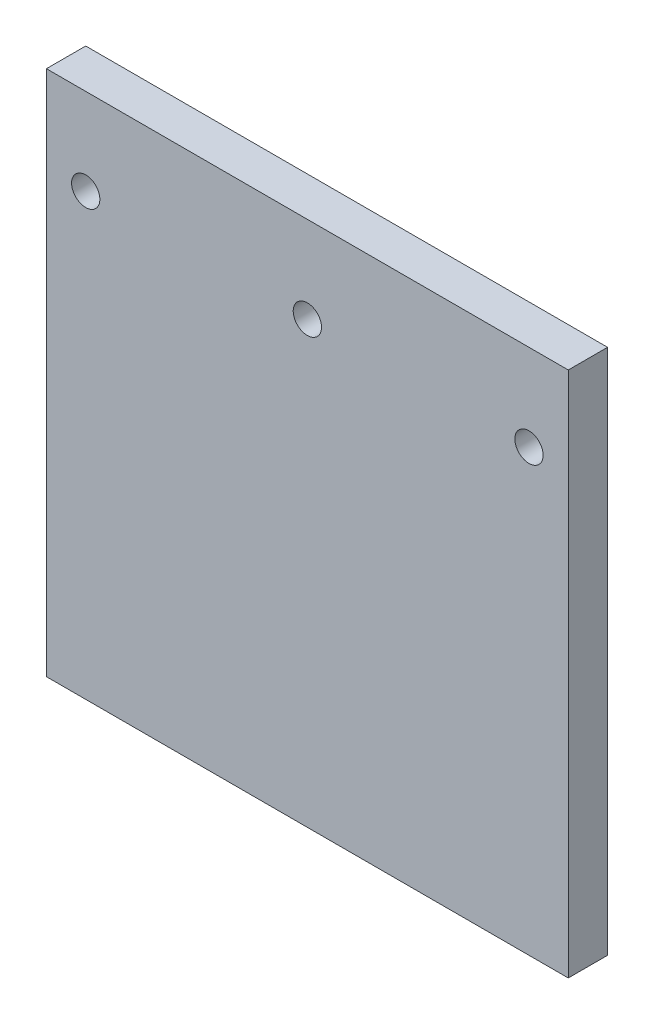
SolidWorks part; units mm, degrees
ref_plane "前视基准面" through (0, 0, 0) normal (0, 0, 1) x (1, 0, 0)
ref_plane "上视基准面" through (0, 0, 0) normal (0, 1, 0) x (1, 0, 0)
ref_plane "右视基准面" through (0, 0, 0) normal (1, 0, 0) x (0, 0, -1)
sketch "Sketch1" plane through (0, 0, 0) normal (0, 1, 0) x (1, 0, 0)
  line L1 (0, 0) -> (50, 0)
  line L2 (0, 0) -> (0, 9.1)
  line L3 (0, 9.1) -> (50, 9.1)
  line L4 (50, 0) -> (50, 9.1)
  dimension "D1" = 50
  dimension "D2" = 9.1
extrude "Boss-Extrude1" add sketch "Sketch1" along normal blind 2
sketch "Sketch2" plane through (0, 2, 0) normal (0, 1, 0) x (1, 0, 0)
  line L0 (50, 9.1) -> (0, 9.1) construction
  line L1 (12.5, 9.1) -> (37.5, 9.1)
  line L2 (12.5, 9.1) -> (12.5, 2.5)
  line L3 (12.5, 2.5) -> (37.5, 2.5)
  line L4 (37.5, 9.1) -> (37.5, 2.5)
  line L5 (0, 9.1) -> (0, 0) construction
  line L6 (50, 0) -> (50, 9.1) construction
  point P8 (50, 4.55)
  dimension "D1" = 6.6
  dimension "D2" = 12.5
  dimension "D3" = 12.5
extrude "Cut-Extrude1" cut sketch "Sketch2" against normal blind 2
sketch "Sketch3" plane through (0, 2, 0) normal (0, 1, 0) x (1, 0, 0)
  line L0 (12.5, 9.1) -> (0, 9.1) construction
  line L1 (50, 9.1) -> (37.5, 9.1) construction
  line L3 (37.5, 2.5) -> (37.5, 9.1) construction
  line L5 (0, 9.1) -> (0, 0) construction
  circle A0 centre (6.25, 5.8) radius 1.8
  circle A1 centre (43.75, 5.8) radius 1.8
  dimension "D1" = 3.6
  dimension "D2" = 3.6
  dimension "D4" = 3.3
  dimension "D3" = 3.3
  dimension "D5" = 6.25
  dimension "D6" = 6.25
extrude "Cut-Extrude2" cut sketch "Sketch3" against normal blind 2
sketch "Sketch4" plane through (0, 2, 0) normal (0, 1, 0) x (1, 0, 0)
  line L0 (0, 0) -> (50, 0) construction
  line L1 (-8.2, 0) -> (58.2, 0)
  line L2 (-8.2, 0) -> (-8.2, -130)
  line L3 (-8.2, -130) -> (58.2, -130)
  line L4 (58.2, 0) -> (58.2, -130)
  line L5 (12.5, 2.5) -> (37.5, 2.5) construction
  point P6 (25, 2.5)
  dimension "D1" = 130
  dimension "D2" = 0
  dimension "D3" = 33.2
  dimension "D4" = 66.4
extrude "Boss-Extrude2" add sketch "Sketch4" against normal blind 2
sketch "Sketch5" plane through (0, 0, 130) normal (0, 0, 1) x (1, 0, 0)
  line L1 (-8.2, 2) -> (58.2, 2)
  line L2 (-8.2, 2) -> (-8.2, 0)
  line L3 (-8.2, 0) -> (58.2, 0)
  line L4 (58.2, 2) -> (58.2, 0)
extrude "Boss-Extrude3" add sketch "Sketch5" along normal blind 2.5
sketch "Sketch6" plane through (0, 2, 0) normal (0, 1, 0) x (1, 0, 0)
  line L1 (-8.2, -132.5) -> (-16.8, -132.5)
  line L2 (-8.2, -132.5) -> (-8.2, -70)
  line L3 (-8.2, -70) -> (-16.8, -70)
  line L4 (-16.8, -132.5) -> (-16.8, -70)
  line L5 (58.2, -132.5) -> (66.8, -132.5)
  line L6 (58.2, -132.5) -> (58.2, -70)
  line L7 (58.2, -70) -> (66.8, -70)
  line L8 (66.8, -132.5) -> (66.8, -70)
  dimension "D1" = 8.6
  dimension "D2" = 8.6
  dimension "D3" = 62.5
  dimension "D4" = 62.5
extrude "Boss-Extrude4" add sketch "Sketch6" against normal blind 2
sketch "Sketch7" plane through (0, 2, 0) normal (0, 1, 0) x (1, 0, 0)
  line L0 (-13.5, -64.2883) -> (-13.5, -157.5169) construction
  line L1 (63.5, -64.2883) -> (63.5, -152.5529) construction
  line L2 (-16.8, -70) -> (-16.8, -132.5) construction
  line L3 (66.8, -132.5) -> (66.8, -70) construction
  line L4 (-8.2, -70) -> (-16.8, -70) construction
  line L5 (66.8, -132.5) -> (-16.8, -132.5) construction
  line L6 (66.8, -70) -> (58.2, -70) construction
  line L7 (-15, -115) -> (-12, -115)
  line L8 (-15, -115) -> (-15, -120)
  line L9 (-15, -120) -> (-12, -120)
  line L10 (-12, -115) -> (-12, -120)
  line L11 (62, -115) -> (65, -115)
  line L12 (62, -115) -> (62, -120)
  line L13 (62, -120) -> (65, -120)
  line L14 (65, -115) -> (65, -120)
  circle A0 centre (-13.5, -77) radius 1.8
  circle A1 centre (-13.5, -101.25) radius 1.8
  circle A2 centre (-13.5, -125.5) radius 1.8
  circle A3 centre (63.5, -77) radius 1.8
  circle A4 centre (63.5, -101.25) radius 1.8
  circle A5 centre (63.5, -125.5) radius 1.8
  dimension "D3" = 3.6
  dimension "D4" = 3.6
  dimension "D6" = 3.6
  dimension "D12" = 3.6
  dimension "D13" = 3.6
  dimension "D14" = 3.6
  dimension "D1" = 3.3
  dimension "D2" = 3.3
  dimension "D5" = 31.25
  dimension "D7" = 7
  dimension "D8" = 1.5
  dimension "D9" = 3
  dimension "D10" = 5
  dimension "D11" = 12.5
  dimension "D15" = 1.5
  dimension "D16" = 3
  dimension "D17" = 7
  dimension "D18" = 7
extrude "Cut-Extrude3" cut sketch "Sketch7" against normal blind 2
sketch "Sketch8" plane through (0, 2, 0) normal (0, 1, 0) x (1, 0, 0)
  line L0 (25, 2.5) -> (25, -143.8166) construction
  line L1 (12.5, 2.5) -> (37.5, 2.5) construction
  line L3 (12.5, 0) -> (37.5, 0)
  line L4 (12.5, 0) -> (12.5, -45)
  line L5 (12.5, -45) -> (37.5, -45)
  line L6 (37.5, 0) -> (37.5, -45)
  dimension "D1" = 25
  dimension "D2" = 12.5
  dimension "D3" = 45
extrude "Cut-Extrude4" cut sketch "Sketch8" against normal blind 20
sketch "Sketch9" plane through (0, 2, 0) normal (0, 1, 0) x (1, 0, 0)
  line L0 (37.5, -45) -> (37.5, 0) construction
  line L1 (12.5, 0) -> (37.5, 0)
  line L2 (12.5, 0) -> (12.5, -10)
  line L3 (12.5, -10) -> (37.5, -10)
  line L4 (37.5, 0) -> (37.5, -10)
  dimension "D1" = 10
extrude "Boss-Extrude5" add sketch "Sketch9" against normal blind 2
sketch "Sketch10" plane through (0, 2, 0) normal (0, 1, 0) x (1, 0, 0)
  line L0 (-8.2, 0) -> (-8.2, -70) construction
  line L1 (-8.2, -16) -> (-42.9, -16)
  line L2 (-8.2, -16) -> (-8.2, -43.07)
  line L3 (-8.2, -43.07) -> (-42.9, -43.07)
  line L4 (-42.9, -16) -> (-42.9, -43.07)
  line L5 (0, 0) -> (-8.2, 0) construction
  line L6 (58.2, -70) -> (58.2, 0) construction
  line L7 (58.2, -16) -> (92.9, -16)
  line L8 (58.2, -16) -> (58.2, -43.07)
  line L9 (58.2, -43.07) -> (92.9, -43.07)
  line L10 (92.9, -16) -> (92.9, -43.07)
  dimension "D1" = 16
  dimension "D2" = 27.07
  dimension "D3" = 34.7
  dimension "D4" = 34.7
extrude "Boss-Extrude6" add sketch "Sketch10" against normal blind 2
sketch "Sketch11" plane through (0, 2, 0) normal (0, 1, 0) x (1, 0, 0)
  line L0 (-48.2559, -39.82) -> (25.7485, -39.82) construction
  line L1 (-47.1851, -19.25) -> (20.7514, -19.25) construction
  line L2 (-8.2, -16) -> (-42.9, -16) construction
  line L3 (-42.9, -43.07) -> (-8.2, -43.07) construction
  line L4 (-42.9, -16) -> (-42.9, -43.07) construction
  circle A0 centre (-36.9, -19.25) radius 1.8
  circle A1 centre (-36.9, -39.82) radius 1.8
  circle A2 centre (-22.6, -19.25) radius 1.8
  circle A3 centre (-22.6, -39.82) radius 1.8
  dimension "D5" = 3.6
  dimension "D6" = 3.6
  dimension "D7" = 3.6
  dimension "D8" = 3.6
  dimension "D10" = 20.3
  dimension "D1" = 3.25
  dimension "D2" = 3.25
  dimension "D3" = 6
  dimension "D4" = 6
  dimension "D9" = 20.3
extrude "Cut-Extrude5" cut sketch "Sketch11" against normal blind 2
sketch "Sketch12" plane through (0, 2, 0) normal (0, 1, 0) x (1, 0, 0)
  line L0 (39.2942, -19.25) -> (115.8735, -19.25) construction
  line L1 (40.8036, -39.82) -> (109.9769, -39.82) construction
  line L2 (92.9, -43.07) -> (92.9, -16) construction
  circle A0 centre (72.6, -19.25) radius 1.8
  circle A1 centre (86.9, -19.25) radius 1.8
  circle A2 centre (72.6, -39.82) radius 1.8
  circle A3 centre (86.9, -39.82) radius 1.8
  dimension "D1" = 3.6
  dimension "D2" = 3.6
  dimension "D5" = 3.6
  dimension "D6" = 3.6
  dimension "D3" = 6
  dimension "D4" = 20.3
extrude "Cut-Extrude6" cut sketch "Sketch12" against normal blind 2
sketch "Sketch13" plane through (-42.9, 0, 0) normal (-1, 0, 0) x (0, 0, 1)
  line L1 (16, 2) -> (14, 2)
  line L2 (16, 2) -> (16, 0)
  line L3 (16, 0) -> (14, 0)
  line L4 (14, 2) -> (14, 0)
  line L5 (43.07, 2) -> (45.07, 2)
  line L6 (43.07, 2) -> (43.07, 0)
  line L7 (43.07, 0) -> (45.07, 0)
  line L8 (45.07, 2) -> (45.07, 0)
  dimension "D1" = 2
  dimension "D2" = 2
extrude "Boss-Extrude7" add sketch "Sketch13" against normal blind 44
sketch "Sketch14" plane through (92.9, 0, 0) normal (1, 0, 0) x (0, 0, -1)
  line L1 (-16, 2) -> (-14, 2)
  line L2 (-16, 2) -> (-16, 0)
  line L3 (-16, 0) -> (-14, 0)
  line L4 (-14, 2) -> (-14, 0)
  line L5 (-43.07, 0) -> (-45.07, 0)
  line L6 (-43.07, 0) -> (-43.07, 2)
  line L7 (-43.07, 2) -> (-45.07, 2)
  line L8 (-45.07, 0) -> (-45.07, 2)
  dimension "D1" = 2
  dimension "D2" = 2
extrude "Boss-Extrude8" add sketch "Sketch14" against normal blind 46
sketch "Sketch16" plane through (0, 2, 0) normal (0, 1, 0) x (1, 0, 0)
  line L0 (66.8, -132.5) -> (-16.8, -132.5) construction
  line L1 (4, -132.5) -> (46, -132.5)
  line L2 (4, -132.5) -> (4, -175.5)
  line L3 (4, -175.5) -> (46, -175.5)
  line L4 (46, -132.5) -> (46, -175.5)
  line L5 (37.5, -45) -> (12.5, -45) construction
  point P6 (25, -45)
  dimension "D1" = 42
  dimension "D2" = 43
  dimension "D3" = 21
extrude "Boss-Extrude10" add sketch "Sketch16" against normal blind 2
sketch "Sketch18" plane through (0, 2, 0) normal (0, 1, 0) x (1, 0, 0)
  line L0 (4, -175.5) -> (46, -175.5) construction
  line L1 (4, -132.5) -> (4, -175.5) construction
  line L2 (46, -175.5) -> (46, -132.5) construction
  line L3 (4, -132.5) -> (-16.8, -132.5) construction
  line L4 (66.8, -132.5) -> (46, -132.5) construction
  circle A0 centre (8.74, -171.03) radius 1.8
  circle A1 centre (41.26, -171.03) radius 1.8
  circle A2 centre (8.74, -138.5) radius 1.8
  circle A3 centre (41.26, -138.5) radius 1.8
  dimension "D3" = 3.6
  dimension "D6" = 3.6
  dimension "D7" = 3.6
  dimension "D8" = 3.6
  dimension "D1" = 4.47
  dimension "D2" = 4.74
  dimension "D4" = 4.47
  dimension "D5" = 4.74
  dimension "D9" = 6
  dimension "D10" = 6
extrude "Cut-Extrude7" cut sketch "Sketch18" against normal blind 2
sketch "Sketch20" plane through (0, 2, 0) normal (0, 1, 0) x (1, 0, 0)
  line L0 (-2, -132.5) -> (4, -132.5)
  line L1 (4, -132.5) -> (-16.8, -132.5) construction
  line L2 (4, -132.5) -> (4, -138.5)
  line L3 (4, -132.5) -> (4, -175.5) construction
  line L4 (46, -138.5) -> (46, -132.5)
  line L5 (46, -175.5) -> (46, -132.5) construction
  line L6 (46, -132.5) -> (52, -132.5)
  line L7 (66.8, -132.5) -> (46, -132.5) construction
  arc A0 (-2, -132.5) -> (4, -138.5) centre (-2, -138.5) cw
  arc A1 (52, -132.5) -> (46, -138.5) centre (52, -138.5) ccw
  dimension "D1" = 6
  dimension "D2" = 6
  dimension "D3" = 6
extrude "Boss-Extrude12" add sketch "Sketch20" against normal blind 2 contours L0 A0 L2 | A1 L6 L4
sketch "Sketch21" plane through (0, 0, -9.1) normal (0, 0, -1) x (-1, 0, 0)
  line L1 (-50, 2) -> (-52, 2)
  line L2 (-50, 2) -> (-50, 0)
  line L3 (-50, 0) -> (-52, 0)
  line L4 (-52, 2) -> (-52, 0)
  line L5 (-37.5, 2) -> (-35.5, 2)
  line L6 (-37.5, 2) -> (-37.5, 0)
  line L7 (-37.5, 0) -> (-35.5, 0)
  line L8 (-35.5, 2) -> (-35.5, 0)
  line L9 (-12.5, 2) -> (-14.5, 2)
  line L10 (-12.5, 2) -> (-12.5, 0)
  line L11 (-12.5, 0) -> (-14.5, 0)
  line L12 (-14.5, 2) -> (-14.5, 0)
  line L13 (0, 2) -> (2, 2)
  line L14 (0, 2) -> (0, 0)
  line L15 (0, 0) -> (2, 0)
  line L16 (2, 2) -> (2, 0)
  dimension "D1" = 2
  dimension "D2" = 2
  dimension "D3" = 2
  dimension "D4" = 2
extrude "Boss-Extrude13" add sketch "Sketch21" against normal blind 10
sketch "Sketch25" plane through (0, 2, 0) normal (0, 1, 0) x (1, 0, 0)
  line L0 (-11.7, -6.4239) -> (-11.7, -56.5762) construction
  line L1 (-8.2, 0) -> (-8.2, -14) construction
  line L2 (61.7, -6.4239) -> (61.7, -56.5762) construction
  line L3 (58.2, -14) -> (58.2, 0) construction
  line L4 (-8.2, -14) -> (-42.9, -14) construction
  line L5 (-13.2, -20) -> (-10.2, -20)
  line L6 (-13.2, -20) -> (-13.2, -25)
  line L7 (-13.2, -25) -> (-10.2, -25)
  line L8 (-10.2, -20) -> (-10.2, -25)
  line L9 (-8.2, -45.07) -> (-42.9, -45.07) construction
  line L10 (-13.2, -34.07) -> (-10.2, -34.07)
  line L11 (-13.2, -34.07) -> (-13.2, -39.07)
  line L12 (-13.2, -39.07) -> (-10.2, -39.07)
  line L13 (-10.2, -34.07) -> (-10.2, -39.07)
  line L14 (58.2, -14) -> (92.9, -14) construction
  line L15 (60.2, -20) -> (63.2, -20)
  line L16 (60.2, -20) -> (60.2, -25)
  line L17 (60.2, -25) -> (63.2, -25)
  line L18 (63.2, -20) -> (63.2, -25)
  line L19 (60.2, -34.07) -> (63.2, -34.07)
  line L20 (60.2, -34.07) -> (60.2, -39.07)
  line L21 (60.2, -39.07) -> (63.2, -39.07)
  line L22 (63.2, -34.07) -> (63.2, -39.07)
  line L23 (58.2, -45.07) -> (92.9, -45.07) construction
  dimension "D1" = 3.5
  dimension "D2" = 3.5
  dimension "D3" = 3
  dimension "D4" = 1.5
  dimension "D5" = 5
  dimension "D6" = 6
  dimension "D7" = 5
  dimension "D8" = 6
  dimension "D9" = 3
  dimension "D10" = 1.5
  dimension "D11" = 1.5
  dimension "D12" = 3
  dimension "D13" = 1.5
  dimension "D14" = 3
  dimension "D15" = 6
  dimension "D16" = 6
extrude "Cut-Extrude8" cut sketch "Sketch25" against normal blind 10
sketch "Sketch26" plane through (0, 2, 0) normal (0, 1, 0) x (1, 0, 0)
  line L1 (-2, 0) -> (-8.2, 0)
  line L2 (-2, 0) -> (-2, 13)
  line L3 (-2, 13) -> (-8.2, 13)
  line L4 (-8.2, 0) -> (-8.2, 13)
  line L5 (58.2, 0) -> (52, 0)
  line L6 (58.2, 0) -> (58.2, 13)
  line L7 (58.2, 13) -> (52, 13)
  line L8 (52, 0) -> (52, 13)
  line L9 (-2, 13) -> (52, 13)
  line L10 (-2, 13) -> (-2, 9.1)
  line L11 (-2, 9.1) -> (52, 9.1)
  line L12 (52, 13) -> (52, 9.1)
  line L13 (35.5, 2.5) -> (14.5, 2.5)
  line L14 (35.5, 2.5) -> (35.5, 9.1)
  line L15 (35.5, 9.1) -> (14.5, 9.1)
  line L16 (14.5, 2.5) -> (14.5, 9.1)
  dimension "D1" = 13
extrude "Boss-Extrude14" add sketch "Sketch26" against normal blind 2 contours L4 L1 L2 L3 | L2 L11 L8 L9 | L16 L13 L14 L11 | L8 L5 L6 L7
sketch "Sketch27" plane through (0, 2, 0) normal (0, 1, 0) x (1, 0, 0)
  line L0 (-8.2, -14) -> (-42.9, -14) construction
  line L1 (-8.2, 13) -> (-10.2, 13)
  line L2 (-8.2, 13) -> (-8.2, -14)
  line L3 (-8.2, -14) -> (-10.2, -14)
  line L4 (-10.2, 13) -> (-10.2, -14)
  line L5 (-8.2, -45.07) -> (-42.9, -45.07) construction
  line L6 (-10.2, -45.07) -> (-8.2, -45.07)
  line L7 (-10.2, -45.07) -> (-10.2, -70)
  line L8 (-10.2, -70) -> (-8.2, -70)
  line L9 (-8.2, -45.07) -> (-8.2, -70)
  line L10 (58.2, -14) -> (92.9, -14) construction
  line L11 (58.2, 13) -> (60.2, 13)
  line L12 (58.2, 13) -> (58.2, -14)
  line L13 (58.2, -14) -> (60.2, -14)
  line L14 (60.2, 13) -> (60.2, -14)
  line L15 (66.8, -70) -> (58.2, -70) construction
  line L16 (58.2, -45.07) -> (60.2, -45.07)
  line L17 (58.2, -45.07) -> (58.2, -70)
  line L18 (58.2, -70) -> (60.2, -70)
  line L19 (60.2, -45.07) -> (60.2, -70)
extrude "Boss-Extrude15" add sketch "Sketch27" against normal blind 2
sketch "Sketch29" plane through (0, 2, 0) normal (0, 1, 0) x (1, 0, 0)
  line L1 (-10.2, -14) -> (-20.2, -14)
  line L2 (-10.2, -14) -> (-10.2, -4)
  line L3 (-10.2, -4) -> (-20.2, -4)
  line L4 (-20.2, -14) -> (-20.2, -4)
  line L5 (-10.2, -45.07) -> (-20.2, -45.07)
  line L6 (-10.2, -45.07) -> (-10.2, -55.07)
  line L7 (-10.2, -55.07) -> (-20.2, -55.07)
  line L8 (-20.2, -45.07) -> (-20.2, -55.07)
  line L9 (60.2, -14) -> (70.2, -14)
  line L10 (60.2, -14) -> (60.2, -4)
  line L11 (60.2, -4) -> (70.2, -4)
  line L12 (70.2, -14) -> (70.2, -4)
  line L13 (60.2, -45.07) -> (70.2, -45.07)
  line L14 (60.2, -45.07) -> (60.2, -55.07)
  line L15 (60.2, -55.07) -> (70.2, -55.07)
  line L16 (70.2, -45.07) -> (70.2, -55.07)
  dimension "D1" = 10
  dimension "D2" = 10
  dimension "D3" = 10
  dimension "D4" = 10
  dimension "D5" = 10
  dimension "D6" = 10
  dimension "D7" = 10
extrude "Boss-Extrude19" add sketch "Sketch29" against normal blind 2
sketch "Sketch41" plane through (0, 2, 0) normal (0, 1, 0) x (1, 0, 0)
  circle A0 centre (-15.2, -9) radius 1.8
  circle A1 centre (-15.2, -50.07) radius 1.8
  circle A2 centre (65.2, -9) radius 1.8
  circle A3 centre (65.2, -50.07) radius 1.8
  dimension "D1" = 3.6
  dimension "D2" = 3.6
  dimension "D3" = 3.6
  dimension "D4" = 3.6
extrude "Cut-Extrude15" cut sketch "Sketch41" against normal blind 2
sketch "Sketch42" plane through (0, 2, 0) normal (0, 1, 0) x (1, 0, 0)
  line L0 (60.2, -70) -> (60.2, -55.07) construction
  line L1 (-10.2, -70) -> (-16.8, -70) construction
  line L2 (-16.8, -70) -> (-10.2, -70)
  line L3 (-10.2, -70) -> (-10.2, -63.4)
  line L4 (60.2, -63.4) -> (60.2, -70)
  line L5 (60.2, -70) -> (66.8, -70)
  arc A0 (-16.8, -70) -> (-10.2, -63.4) centre (-16.8, -63.4) ccw
  arc A1 (66.8, -70) -> (60.2, -63.4) centre (66.8, -63.4) cw
  dimension "D1" = 6.6
extrude "Boss-Extrude26" add sketch "Sketch42" against normal blind 2
sketch "Sketch43" plane through (0, 0, -13) normal (0, 0, -1) x (-1, 0, 0)
  line L1 (10.2, 2) -> (-60.2, 2)
  line L2 (10.2, 2) -> (10.2, 0)
  line L3 (10.2, 0) -> (-60.2, 0)
  line L4 (-60.2, 2) -> (-60.2, 0)
extrude "Boss-Extrude27" add sketch "Sketch43" along normal blind 11
sketch "Sketch44" plane through (0, 2, 0) normal (0, 1, 0) x (1, 0, 0)
  line L0 (-10.2, -55.07) -> (-10.2, -63.4) construction
  line L1 (-20.2, -55.07) -> (-10.2, -55.07)
  line L2 (-20.2, -55.07) -> (-20.2, -60.07)
  line L3 (-20.2, -60.07) -> (-10.2, -60.07)
  line L4 (-10.2, -55.07) -> (-10.2, -60.07)
  line L5 (60.2, -63.4) -> (60.2, -55.07) construction
  line L6 (70.2, -55.07) -> (60.2, -55.07)
  line L7 (70.2, -55.07) -> (70.2, -60.07)
  line L8 (70.2, -60.07) -> (60.2, -60.07)
  line L9 (60.2, -55.07) -> (60.2, -60.07)
  dimension "D1" = 5
extrude "Boss-Extrude28" add sketch "Sketch44" against normal blind 2
sketch "Sketch45" plane through (0, 2, 0) normal (0, 1, 0) x (1, 0, 0)
  circle A0 centre (-15.2, -50.07) radius 1.8
  circle A1 centre (65.2, -50.07) radius 1.8
extrude "Boss-Extrude29" add sketch "Sketch45" against normal blind 2
sketch "Sketch46" plane through (0, 2, 0) normal (0, 1, 0) x (1, 0, 0)
  line L0 (-20.2, -60.07) -> (-10.2, -60.07) construction
  line L1 (60.2, -60.07) -> (70.2, -60.07) construction
  line L2 (-20.2, -45.07) -> (-20.2, -60.07) construction
  line L3 (70.2, -60.07) -> (70.2, -45.07) construction
  circle A0 centre (-15.2, -55.07) radius 1.8
  circle A1 centre (65.2, -55.07) radius 1.8
  dimension "D2" = 3.6
  dimension "D3" = 3.6
  dimension "D1" = 5
  dimension "D4" = 5
  dimension "D5" = 5
  dimension "D6" = 5
extrude "Cut-Extrude16" cut sketch "Sketch46" against normal blind 2
sketch "Sketch47" plane through (0, 2, 0) normal (0, 1, 0) x (1, 0, 0)
  line L0 (-10.2, 24) -> (-10.2, -4) construction
  line L1 (-20.2, -4) -> (-10.2, -4)
  line L2 (-20.2, -4) -> (-20.2, -3)
  line L3 (-20.2, -3) -> (-10.2, -3)
  line L4 (-10.2, -4) -> (-10.2, -3)
  line L5 (-10.2, -60.07) -> (-10.2, -63.4) construction
  line L6 (-20.2, -60.07) -> (-10.2, -60.07)
  line L7 (-20.2, -60.07) -> (-20.2, -61.07)
  line L8 (-20.2, -61.07) -> (-10.2, -61.07)
  line L9 (-10.2, -60.07) -> (-10.2, -61.07)
  line L10 (60.2, -63.4) -> (60.2, -60.07) construction
  line L11 (60.2, -4) -> (70.2, -4)
  line L12 (60.2, -4) -> (60.2, -3)
  line L13 (60.2, -3) -> (70.2, -3)
  line L14 (70.2, -4) -> (70.2, -3)
  line L15 (70.2, -60.07) -> (60.2, -60.07)
  line L16 (70.2, -60.07) -> (70.2, -61.07)
  line L17 (70.2, -61.07) -> (60.2, -61.07)
  line L18 (60.2, -60.07) -> (60.2, -61.07)
  dimension "D1" = 1
  dimension "D2" = 1
extrude "Boss-Extrude30" add sketch "Sketch47" against normal blind 2
sketch "Sketch48" plane through (0, 2, 0) normal (0, 1, 0) x (1, 0, 0)
  line L1 (-42.9, -14) -> (-10.2, -14)
  line L2 (-42.9, -14) -> (-42.9, -45.07)
  line L3 (-42.9, -45.07) -> (-10.2, -45.07)
  line L4 (-10.2, -14) -> (-10.2, -45.07)
  line L5 (92.9, -14) -> (60.2, -14)
  line L6 (92.9, -14) -> (92.9, -45.07)
  line L7 (92.9, -45.07) -> (60.2, -45.07)
  line L8 (60.2, -14) -> (60.2, -45.07)
  line L9 (-20.2, -61.07) -> (81.55, -61.07)
  line L10 (-20.2, -61.07) -> (-20.2, -181.5574)
  line L11 (-20.2, -181.5574) -> (81.55, -181.5574)
  line L12 (81.55, -61.07) -> (81.55, -181.5574)
extrude "Cut-Extrude17" cut sketch "Sketch48" against normal blind 20
sketch "Sketch50" plane through (0, 2, 0) normal (0, 1, 0) x (1, 0, 0)
  line L0 (-10.2, 24) -> (-10.2, -3) construction
  line L1 (-8.2, 22) -> (58.2, 22)
  line L2 (-8.2, 22) -> (-8.2, -59.07)
  line L3 (-8.2, -59.07) -> (58.2, -59.07)
  line L4 (58.2, 22) -> (58.2, -59.07)
  line L5 (-10.2, 24) -> (60.2, 24) construction
  line L6 (-20.2, -61.07) -> (70.2, -61.07) construction
  line L7 (60.2, -3) -> (60.2, 24) construction
  dimension "D1" = 2
  dimension "D2" = 2
  dimension "D3" = 2
  dimension "D4" = 2
extrude "Cut-Extrude19" cut sketch "Sketch50" against normal blind 20
sketch "Sketch51" plane through (0, 2, 0) normal (0, 1, 0) x (1, 0, 0)
  line L0 (-20.2, -61.07) -> (70.2, -61.07) construction
  line L1 (-10.2, 24) -> (60.2, 24)
  line L2 (-10.2, 24) -> (-10.2, -61.07)
  line L3 (-10.2, -61.07) -> (60.2, -61.07)
  line L4 (60.2, 24) -> (60.2, -61.07)
  line L6 (58.2, -59.07) -> (-8.2, -59.07)
  line L7 (58.2, -59.07) -> (58.2, 22)
  line L8 (58.2, 22) -> (-8.2, 22)
  line L9 (-8.2, -59.07) -> (-8.2, 22)
extrude "Boss-Extrude31" add sketch "Sketch51" along normal blind 20
sketch "Sketch52" plane through (0, 2, 0) normal (0, 1, 0) x (1, 0, 0)
  line L0 (-10.2, 24) -> (-10.2, -61.07) construction
  line L1 (-20.2, -14) -> (-10.2, -14)
  line L2 (-20.2, -14) -> (-20.2, -15)
  line L3 (-20.2, -15) -> (-10.2, -15)
  line L4 (-10.2, -14) -> (-10.2, -15)
  line L5 (60.2, -61.07) -> (60.2, 24) construction
  line L6 (70.2, -14) -> (60.2, -14)
  line L7 (70.2, -14) -> (70.2, -15)
  line L8 (70.2, -15) -> (60.2, -15)
  line L9 (60.2, -14) -> (60.2, -15)
  dimension "D1" = 1
extrude "Boss-Extrude32" add sketch "Sketch52" against normal blind 2
sketch "Sketch53" plane through (0, 2, 0) normal (0, 1, 0) x (1, 0, 0)
  line L0 (-10.2, 24) -> (-10.2, -61.07) construction
  line L1 (-20.2, -45.07) -> (-10.2, -45.07)
  line L2 (-20.2, -45.07) -> (-20.2, -49.07)
  line L3 (-20.2, -49.07) -> (-10.2, -49.07)
  line L4 (-10.2, -45.07) -> (-10.2, -49.07)
  line L5 (60.2, -61.07) -> (60.2, 24) construction
  line L6 (70.2, -45.07) -> (60.2, -45.07)
  line L7 (70.2, -45.07) -> (70.2, -49.07)
  line L8 (70.2, -49.07) -> (60.2, -49.07)
  line L9 (60.2, -45.07) -> (60.2, -49.07)
  dimension "D1" = 4
  dimension "D2" = 4
extrude "Cut-Extrude20" cut sketch "Sketch53" against normal blind 2
sketch "Sketch54" plane through (0, 2, 0) normal (0, 1, 0) x (1, 0, 0)
  line L1 (-20.2, -3) -> (-10.2, -3)
  line L2 (-20.2, -3) -> (-20.2, -15)
  line L3 (-20.2, -15) -> (-10.2, -15)
  line L4 (-10.2, -3) -> (-10.2, -15)
  line L5 (-20.2, -49.07) -> (-10.2, -49.07)
  line L6 (-20.2, -49.07) -> (-20.2, -61.07)
  line L7 (-20.2, -61.07) -> (-10.2, -61.07)
  line L8 (-10.2, -49.07) -> (-10.2, -61.07)
  line L9 (60.2, -3) -> (70.2, -3)
  line L10 (60.2, -3) -> (60.2, -15)
  line L11 (60.2, -15) -> (70.2, -15)
  line L12 (70.2, -3) -> (70.2, -15)
  line L13 (60.2, -49.07) -> (70.2, -49.07)
  line L14 (60.2, -49.07) -> (60.2, -61.07)
  line L15 (60.2, -61.07) -> (70.2, -61.07)
  line L16 (70.2, -49.07) -> (70.2, -61.07)
  circle A0 centre (-15.2, -9) radius 1.8
  circle A1 centre (-15.2, -55.07) radius 1.8
  circle A2 centre (65.2, -9) radius 1.8
  circle A3 centre (65.2, -55.07) radius 1.8
extrude "Boss-Extrude33" add sketch "Sketch54" along normal blind 1
sketch "Sketch55" plane through (0, 0, 3) normal (0, 0, -1) x (-1, 0, 0)
  line L0 (20.2, 3) -> (10.2, 22)
  line L1 (10.2, 22) -> (10.2, 3)
  line L2 (10.2, 3) -> (20.2, 3)
  line L3 (-70.2, 3) -> (-60.2, 3)
  line L4 (-60.2, 3) -> (-60.2, 22)
  line L5 (-60.2, 22) -> (-70.2, 3)
sketch "Sketch56" plane through (0, 0, 15) normal (0, 0, 1) x (1, 0, 0)
  line L0 (-20.2, 3) -> (-10.2, 3)
  line L1 (-10.2, 3) -> (-10.2, 22)
  line L2 (-10.2, 22) -> (-20.2, 3)
  line L3 (70.2, 3) -> (60.2, 3)
  line L4 (60.2, 3) -> (60.2, 22)
  line L5 (60.2, 22) -> (70.2, 3)
sketch "Sketch57" plane through (0, 0, 49.07) normal (0, 0, -1) x (-1, 0, 0)
  line L0 (20.2, 3) -> (10.2, 3)
  line L1 (10.2, 22) -> (20.2, 3)
  line L2 (-70.2, 3) -> (-60.2, 3)
  line L3 (-60.2, 3) -> (-60.2, 22)
  line L4 (-60.2, 22) -> (-70.2, 3)
  line L5 (10.2, 3) -> (10.2, 22)
sketch "Sketch59" plane through (0, 0, -22) normal (0, 0, 1) x (1, 0, 0)
  line L0 (-8.2, 11) -> (58.2, 11) construction
  line L1 (-8.2, 0) -> (-8.2, 22) construction
  line L2 (58.2, 0) -> (58.2, 22) construction
  circle A0 centre (-3.2, 11) radius 1.8
  circle A1 centre (53.2, 11) radius 1.8
  circle A2 centre (25, 11) radius 1.8
  dimension "D1" = 3.6
  dimension "D2" = 3.6
  dimension "D5" = 3.6
  dimension "D3" = 5
  dimension "D4" = 5
extrude "Cut-Extrude23" cut sketch "Sketch59" against normal blind 16 and the other way blind 96
sketch "Sketch62" plane through (0, 0, 61.07) normal (0, 0, 1) x (1, 0, 0)
  line L1 (-8.5777, 16.369) -> (58.4073, 16.369)
  line L2 (-8.5777, 16.369) -> (-8.5777, 5.1196)
  line L3 (-8.5777, 5.1196) -> (58.4073, 5.1196)
  line L4 (58.4073, 16.369) -> (58.4073, 5.1196)
extrude "Boss-Extrude38" add sketch "Sketch62" against normal blind 1
sketch "Sketch65" plane through (0, 0, 59.07) normal (0, 0, -1) x (-1, 0, 0)
  line L0 (8.2, 11) -> (-58.2, 11) construction
  line L1 (8.2, 0) -> (8.2, 22) construction
  line L2 (-58.2, 0) -> (-58.2, 22) construction
  circle A0 centre (-13.8, 11) radius 1.8
  circle A1 centre (-36.2, 11) radius 1.8
  dimension "D2" = 3.6
  dimension "D4" = 3.6
  dimension "D1" = 22
  dimension "D3" = 22
extrude "Cut-Extrude27" cut sketch "Sketch65" against normal blind 3
sketch "Sketch66" plane through (-10.2, 0, 0) normal (-1, 0, 0) x (0, 0, 1)
  line L0 (-24, 22) -> (61.07, 22) construction
  circle A0 centre (32.035, 16) radius 1
  dimension "D1" = 6
  dimension "D2" = 2
extrude "Cut-Extrude28" cut sketch "Sketch66" against normal blind 87
extrude "Boss-Extrude41" add sketch "Sketch55" against normal blind 2
extrude "Boss-Extrude42" add sketch "Sketch56" against normal blind 2
extrude "Boss-Extrude43" add sketch "Sketch57" against normal blind 2
sketch "Sketch68" plane through (0, 0, 59.07) normal (0, 0, -1) x (-1, 0, 0)
  line L1 (-0.8965, 6.2744) -> (5.8953, 6.2744)
  line L2 (-0.8965, 6.2744) -> (-0.8965, 14.4185)
  line L3 (-0.8965, 14.4185) -> (5.8953, 14.4185)
  line L4 (5.8953, 6.2744) -> (5.8953, 14.4185)
  line L5 (-21.8815, 6.2744) -> (-27.3672, 6.2744)
  line L6 (-21.8815, 6.2744) -> (-21.8815, 14.4185)
  line L7 (-21.8815, 14.4185) -> (-27.3672, 14.4185)
  line L8 (-27.3672, 6.2744) -> (-27.3672, 14.4185)
  line L9 (-48.3497, 6.2744) -> (-56.1137, 6.2744)
  line L10 (-48.3497, 6.2744) -> (-48.3497, 17.9033)
  line L11 (-48.3497, 17.9033) -> (-56.1137, 17.9033)
  line L12 (-56.1137, 6.2744) -> (-56.1137, 17.9033)
extrude "Boss-Extrude44" add sketch "Sketch68" against normal blind 2
sketch "Sketch69" plane through (0, 0, 61.07) normal (0, 0, 1) x (1, 0, 0)
  line L0 (-20.2, 3) -> (-10.2, 3)
  line L1 (-10.2, 3) -> (-10.2, 22)
  line L2 (-10.2, 22) -> (-20.2, 3)
  line L3 (60.2, 3) -> (70.2, 3)
  line L4 (70.2, 3) -> (60.2, 22)
  line L5 (60.2, 22) -> (60.2, 3)
extrude "Boss-Extrude45" add sketch "Sketch69" against normal blind 2
sketch "Sketch70" plane through (-10.2, 0, 0) normal (-1, 0, 0) x (0, 0, 1)
  line L0 (5, 22) -> (13, 22) construction
  circle A0 centre (9, 17) radius 1.8
  circle A1 centre (55.07, 17) radius 1.8
  dimension "D1" = 3.6
  dimension "D3" = 3.6
  dimension "D2" = 5
extrude "Cut-Extrude29" cut sketch "Sketch70" against normal blind 83
sketch "Sketch72" plane through (0, 0, -22) normal (0, 0, 1) x (1, 0, 0)
  line L1 (-21.7706, 22) -> (83.254, 22)
  line L2 (-21.7706, 22) -> (-21.7706, -46.6494)
  line L3 (-21.7706, -46.6494) -> (83.254, -46.6494)
  line L4 (83.254, 22) -> (83.254, -46.6494)
extrude "Cut-Extrude33" cut sketch "Sketch72" along normal blind 92
sketch "Sketch73" plane through (0, 0, -22) normal (0, 0, 1) x (1, 0, 0)
  line L0 (-10.2, 0) -> (60.2, 0) construction
  line L1 (-10.2, 22) -> (-8.2, 22)
  line L2 (-10.2, 22) -> (-10.2, 0)
  line L3 (-10.2, 0) -> (-8.2, 0)
  line L4 (-8.2, 22) -> (-8.2, 0)
  line L6 (60.2, 22) -> (58.2, 22)
  line L7 (60.2, 22) -> (60.2, 0)
  line L8 (60.2, 0) -> (58.2, 0)
  line L9 (58.2, 22) -> (58.2, 0)
  dimension "D1" = 2
  dimension "D2" = 2
extrude "Cut-Extrude34" cut sketch "Sketch73" against normal blind 92
sketch "Sketch74" plane through (0, 0, 0) normal (0, -1, 0) x (-1, 0, 0)
  line L1 (8.2, 22) -> (-58.2, 22)
  line L2 (8.2, 22) -> (8.2, 24)
  line L3 (8.2, 24) -> (-58.2, 24)
  line L4 (-58.2, 22) -> (-58.2, 24)
extrude "Boss-Extrude46" add sketch "Sketch74" along normal blind 45
sketch "Sketch75" plane through (0, 0, -24) normal (0, 0, -1) x (-1, 0, 0)
  line L1 (-58.2, 22) -> (8.2, 22)
  line L2 (-58.2, 22) -> (-58.2, -45)
  line L3 (-58.2, -45) -> (8.2, -45)
  line L4 (8.2, 22) -> (8.2, -45)
  circle A0 centre (-53.2, 11) radius 1.8
  circle A1 centre (-25, 11) radius 1.8
  circle A2 centre (3.2, 11) radius 1.8
extrude "Boss-Extrude47" add sketch "Sketch75" along normal blind 3
